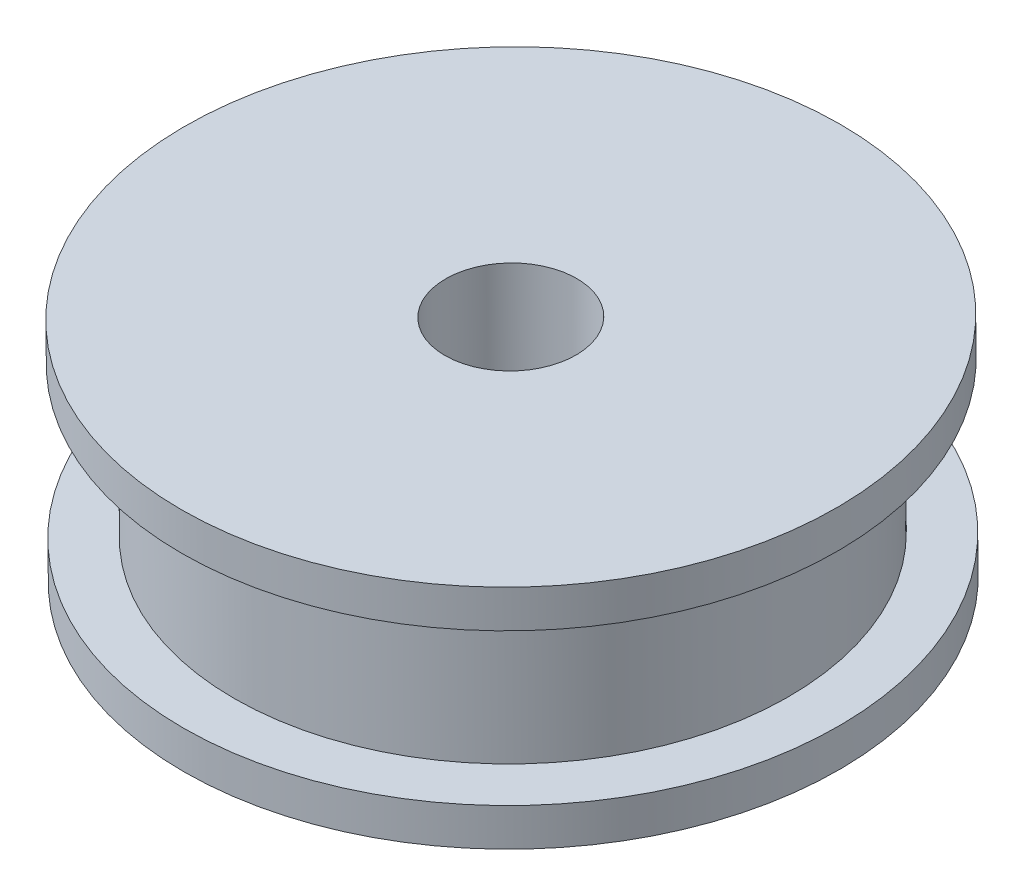
SolidWorks part; units mm, degrees
ref_plane "Front Plane" through (0, 0, 0) normal (0, 0, 1) x (1, 0, 0)
ref_plane "Top Plane" through (0, 0, 0) normal (0, 1, 0) x (1, 0, 0)
ref_plane "Right Plane" through (0, 0, 0) normal (1, 0, 0) x (0, 0, -1)
sketch "Sketch2" plane through (-0.006, 2.8431, 0.0241) normal (-0.0021, 1, 0.0085) x (1, 0.0021, 0)
  circle A0 centre (0, 1.5999) radius 11
  dimension "D1" = 22
extrude "Boss-Extrude1" add sketch "Sketch2" along normal blind 6
sketch "Sketch3" plane through (-0.0188, 8.8429, 0.0748) normal (-0.0021, 1, 0.0085) x (1, 0.0021, 0)
  line L0 (0, -0.1251) -> (0, 1.5999) construction
  line L1 (-1.725, -0.1251) -> (1.725, -0.1251)
  line L2 (-1.725, -0.1251) -> (-1.725, 3.3249)
  line L3 (-1.725, 3.3249) -> (1.725, 3.3249)
  line L4 (1.725, 3.3249) -> (1.725, -0.1251)
  circle A1 centre (0, 1.5999) radius 2.0642 construction
  point P6 (0, -0.1251)
  dimension "D1" = 3.45
  dimension "D2" = 1.725
extrude "Cut-Extrude1" cut sketch "Sketch3" against normal through all
ref_plane "Plane1" through (-0.0124, 5.843, 0.0495) normal (0.0021, -1, -0.0085) x (-1, -0.0021, 0)
sketch "Sketch4" plane through (-0.0188, 8.8429, 0.0748) normal (-0.0021, 1, 0.0085) x (1, 0.0021, 0)
  circle A0 centre (0, 1.5999) radius 13
  dimension "D1" = 26
extrude "Boss-Extrude2" add sketch "Sketch4" along normal blind 1.5
mirror "Mirror1" about plane through (-0.0124, 5.843, 0.0495) normal (0.0021, -1, -0.0085) of "Boss-Extrude2"
sketch "Sketch5" plane through (-0.022, 10.3428, 0.0875) normal (-0.0021, 1, 0.0085) x (1, 0.0021, 0)
  line L4 (-1.725, -0.1251) -> (1.725, -0.1251)
  line L5 (1.725, -0.1251) -> (1.725, 3.3249)
  line L6 (1.725, 3.3249) -> (-1.725, 3.3249)
  line L7 (-1.725, 3.3249) -> (-1.725, -0.1251)
  line L8 (-1.725, -0.1251) -> (1.725, -0.1251)
  line L9 (1.725, -0.1251) -> (1.725, 3.3249)
  line L10 (1.725, 3.3249) -> (-1.725, 3.3249)
  line L11 (-1.725, 3.3249) -> (-1.725, -0.1251)
  dimension "D1" = 0
extrude "Cut-Extrude2" cut sketch "Sketch5" against normal through all
sketch "Sketch6" plane through (-0.022, 10.3428, 0.0875) normal (-0.0021, 1, 0.0085) x (1, 0.0021, 0)
  circle A0 centre (0, 1.5999) radius 2.6
  dimension "D1" = 5.2
extrude "Cut-Extrude3" cut sketch "Sketch6" against normal through all
